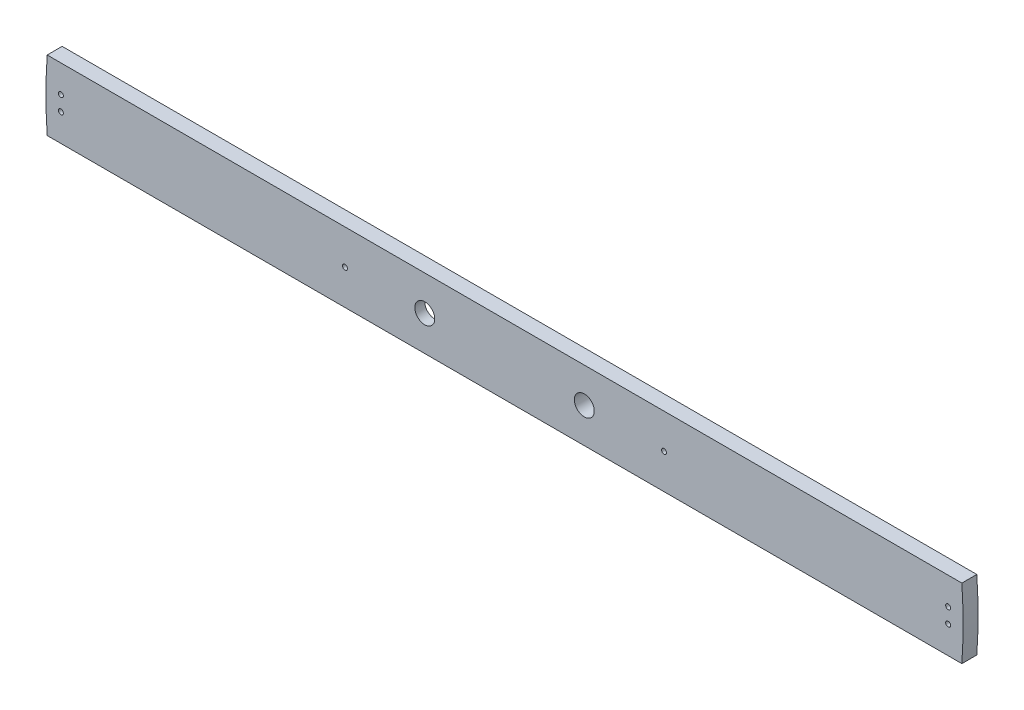
SolidWorks part; units mm, degrees
ref_plane "Front Plane" through (0, 0, 0) normal (0, 0, 1) x (1, 0, 0)
ref_plane "Top Plane" through (0, 0, 0) normal (0, 1, 0) x (1, 0, 0)
ref_plane "Right Plane" through (0, 0, 0) normal (1, 0, 0) x (0, 0, -1)
sketch "Sketch1" plane through (0, 0, 0) normal (0, 0, 1) x (1, 0, 0)
  line L0 (101.6, 0) -> (0, 0) construction
  line L9 (582.5065, 44.45) -> (-582.5065, 44.45)
  line L11 (582.5065, -44.45) -> (-582.5065, -44.45)
  line L13 (582.5065, 44.45) -> (-582.5065, -44.45) construction
  line L14 (582.5065, -44.45) -> (-582.5065, 44.45) construction
  line L15 (0, -44.45) -> (0, 0) construction
  line L16 (0, 0) -> (0, 44.45) construction
  line L17 (0, 0) -> (-580.5114, 0) construction
  arc A0 (582.5065, 44.45) -> (582.5065, -44.45) centre (0, 0) cw
  arc A1 (-582.5065, 44.45) -> (-582.5065, -44.45) centre (0, 0) ccw
  circle A2 centre (101.6, 0) radius 12.7
  circle A3 centre (0, 0) radius 565.15 construction
  circle A4 centre (-565.0697, 9.525) radius 3.175
  circle A5 centre (-565.0697, -9.525) radius 3.175
  circle A6 centre (565.0697, -9.525) radius 3.175
  circle A7 centre (565.0697, 9.525) radius 3.175
  circle A8 centre (0, 0) radius 584.2 construction
  circle A9 centre (-101.6, 0) radius 12.7
  circle A10 centre (-203.2, 0) radius 3.175
  circle A13 centre (203.2, 0) radius 3.175
  point P0 (0, 0)
  point P7 (584.2, 0)
  point P8 (-584.2, 0)
  dimension "D2" = 25.4
  dimension "D7" = 25.4
  dimension "D8" = 1130.3
  dimension "D9" = 6.35
  dimension "D12" = 1168.4
  dimension "D13" = 203.2
  dimension "D3" = 88.9
  dimension "D4" = 1168.4
  dimension "D5" = 101.6
  dimension "D6" = 101.6
  dimension "D10" = 19.05
  dimension "D11" = 9.525
extrude "Boss-Extrude2" add sketch "Sketch1" along normal blind 19.05 contours L9 A1 L11 A0 A2
sketch "Sketch2" plane through (0, 0, 0) normal (0, 0, 1) x (1, 0, 0)
  line L0 (-121.92, 19.05) -> (-101.6, 0) construction
  line L1 (-121.92, 19.05) -> (-81.28, 19.05)
  line L2 (-121.92, 19.05) -> (-121.92, -107.95)
  line L3 (-121.92, -107.95) -> (-81.28, -107.95)
  line L4 (-81.28, 19.05) -> (-81.28, -107.95)
  line L5 (-101.6, 0) -> (-81.28, 19.05) construction
  dimension "D1" = 19.05
  dimension "D2" = 127
  dimension "D3" = 40.64
extrude "Cut-Extrude1" cut sketch "Sketch2" along normal offset from surface (6.35 mm away) 6.35 up to face at (568.2447, 9.525, 0)
